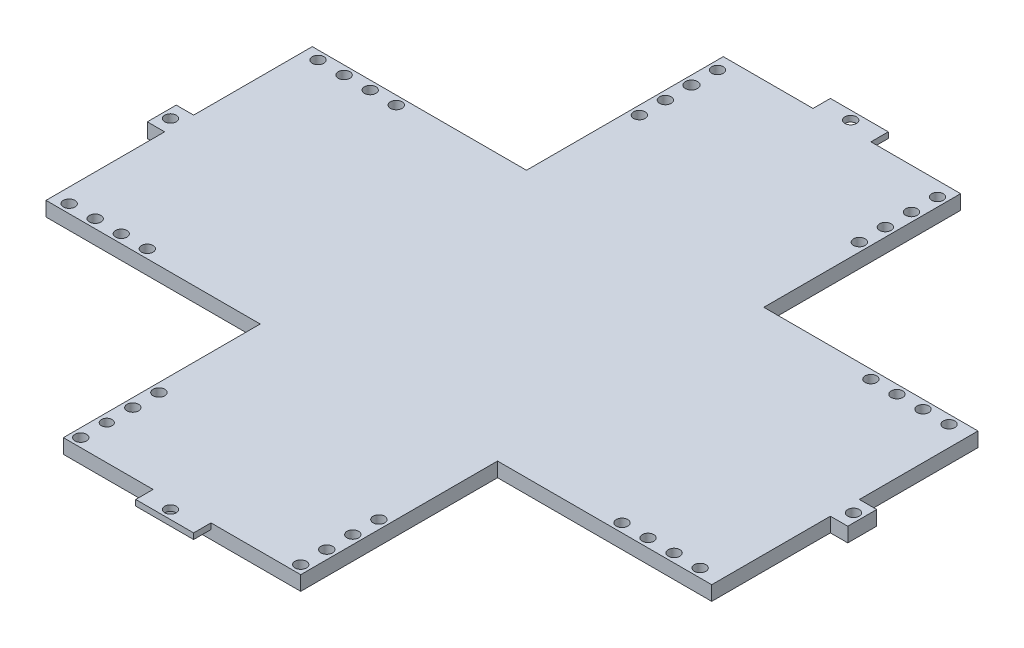
SolidWorks part; units mm, degrees
ref_plane "Front Plane" through (0, 0, 0) normal (0, 0, 1) x (1, 0, 0)
ref_plane "Top Plane" through (0, 0, 0) normal (0, 1, 0) x (1, 0, 0)
ref_plane "Right Plane" through (0, 0, 0) normal (1, 0, 0) x (0, 0, -1)
sketch "Sketch1" plane through (0, 0, 0) normal (0, 1, 0) x (1, 0, 0)
  line L0 (0, 0) -> (0, 233.68)
  line L1 (203.2, 233.68) -> (0, 233.68)
  line L2 (203.2, 233.68) -> (203.2, 421.64)
  line L3 (203.2, 421.64) -> (411.48, 421.64)
  line L4 (411.48, 421.64) -> (411.48, 233.68)
  line L5 (411.48, 233.68) -> (614.68, 233.68)
  line L6 (614.68, 233.68) -> (614.68, 0)
  line L7 (614.68, 0) -> (411.48, 0)
  line L8 (411.48, 0) -> (411.48, -187.96)
  line L9 (411.48, -187.96) -> (203.2, -187.96)
  line L10 (203.2, -187.96) -> (203.2, 0)
  line L11 (203.2, 0) -> (0, 0)
  dimension "D1" = 233.68
  dimension "D2" = 208.28
  dimension "D3" = 203.2
  dimension "D4" = 187.96
  dimension "D5" = 187.96
  dimension "D6" = 203.2
  dimension "D7" = 203.2
  dimension "D8" = 233.68
  dimension "D9" = 187.96
  dimension "D10" = 187.96
  dimension "D11" = 208.28
extrude "Boss-Extrude1" add sketch "Sketch1" along normal blind 12.7
sketch "Sketch3" plane through (0, 12.7, 0) normal (0, 1, 0) x (1, 0, 0)
  line L1 (203.2, 421.64) -> (281.94, 421.64)
  line L2 (203.2, 421.64) -> (203.2, 406.4)
  line L3 (203.2, 406.4) -> (281.94, 406.4)
  line L4 (281.94, 421.64) -> (281.94, 406.4)
  line L5 (411.48, 421.64) -> (332.74, 421.64)
  line L6 (411.48, 421.64) -> (411.48, 406.4)
  line L7 (411.48, 406.4) -> (332.74, 406.4)
  line L8 (332.74, 421.64) -> (332.74, 406.4)
  line L9 (411.48, -187.96) -> (332.74, -187.96)
  line L10 (411.48, -187.96) -> (411.48, -172.72)
  line L11 (411.48, -172.72) -> (332.74, -172.72)
  line L12 (332.74, -187.96) -> (332.74, -172.72)
  line L13 (203.2, -187.96) -> (281.94, -187.96)
  line L14 (203.2, -187.96) -> (203.2, -172.72)
  line L15 (203.2, -172.72) -> (281.94, -172.72)
  line L16 (281.94, -187.96) -> (281.94, -172.72)
extrude "Cut-Extrude1" cut sketch "Sketch3" against normal blind 15.24
sketch "Sketch5" plane through (0, 0, 0) normal (0, -1, 0) x (-1, 0, 0)
  line L0 (-281.94, 421.64) -> (-281.94, 406.4) construction
  line L1 (-281.94, -187.96) -> (-332.74, -187.96)
  line L2 (-281.94, -187.96) -> (-281.94, -172.72)
  line L3 (-281.94, -172.72) -> (-332.74, -172.72)
  line L4 (-332.74, -187.96) -> (-332.74, -172.72)
  line L5 (-332.74, 421.64) -> (-281.94, 421.64)
  line L6 (-332.74, 421.64) -> (-332.74, 406.4)
  line L7 (-332.74, 406.4) -> (-281.94, 406.4)
  line L8 (-281.94, 421.64) -> (-281.94, 406.4)
extrude "Cut-Extrude2" cut sketch "Sketch5" against normal blind 7.62
sketch "Sketch6" plane through (0, 12.7, 0) normal (0, 1, 0) x (1, 0, 0)
  line L0 (281.94, -187.96) -> (332.74, -187.96) construction
  line L1 (332.74, 421.64) -> (281.94, 421.64) construction
  circle A0 centre (307.34, 414.02) radius 5.08
  circle A1 centre (304.8, -180.34) radius 5.08
  point P8 (307.34, 421.64)
  point P9 (0, 0)
  point P10 (0, 0)
  dimension "D1" = 7.62
  dimension "D2" = 7.62
extrude "Cut-Extrude3" cut sketch "Sketch6" against normal blind 10.16
sketch "Sketch7" plane through (0, 12.7, 0) normal (0, 1, 0) x (1, 0, 0)
  line L1 (0, 0) -> (15.24, 0)
  line L2 (0, 0) -> (0, 104.14)
  line L3 (0, 104.14) -> (15.24, 104.14)
  line L4 (15.24, 0) -> (15.24, 104.14)
  line L5 (0, 233.68) -> (15.24, 233.68)
  line L6 (0, 233.68) -> (0, 129.54)
  line L7 (0, 129.54) -> (15.24, 129.54)
  line L8 (15.24, 233.68) -> (15.24, 129.54)
  line L9 (614.68, 0) -> (599.44, 0)
  line L10 (614.68, 0) -> (614.68, 104.14)
  line L11 (614.68, 104.14) -> (599.44, 104.14)
  line L12 (599.44, 0) -> (599.44, 104.14)
  line L13 (614.68, 233.68) -> (599.44, 233.68)
  line L14 (614.68, 233.68) -> (614.68, 129.54)
  line L15 (614.68, 129.54) -> (599.44, 129.54)
  line L16 (599.44, 233.68) -> (599.44, 129.54)
extrude "Cut-Extrude4" cut sketch "Sketch7" against normal blind 15.24
sketch "Sketch8" plane through (0, 12.7, 0) normal (0, 1, 0) x (1, 0, 0)
  circle A0 centre (607.06, 116.84) radius 5.08
  circle A1 centre (7.62, 116.84) radius 5.08
extrude "Cut-Extrude5" cut sketch "Sketch8" against normal blind 15.24
sketch "Sketch9" plane through (0, 12.7, 0) normal (0, 1, 0) x (1, 0, 0)
  line L0 (15.24, 0) -> (15.24, 104.14) construction
  line L1 (203.2, 406.4) -> (281.94, 406.4) construction
  circle A0 centre (27.94, 226.06) radius 5.08
  circle A1 centre (50.8, 226.06) radius 5.08
  circle A2 centre (73.66, 226.06) radius 5.08
  circle A3 centre (96.52, 226.06) radius 5.08
  circle A4 centre (581.66, 226.06) radius 5.08
  circle A5 centre (558.8, 226.06) radius 5.08
  circle A6 centre (535.94, 226.06) radius 5.08
  circle A7 centre (513.08, 226.06) radius 5.08
  circle A8 centre (27.94, 7.62) radius 5.08
  circle A9 centre (50.8, 7.62) radius 5.08
  circle A10 centre (73.66, 7.62) radius 5.08
  circle A11 centre (96.52, 7.62) radius 5.08
  circle A12 centre (581.66, 7.62) radius 5.08
  circle A13 centre (558.8, 7.62) radius 5.08
  circle A14 centre (535.94, 7.62) radius 5.08
  circle A15 centre (513.08, 7.62) radius 5.08
  circle A16 centre (210.82, 393.7) radius 5.08
  circle A17 centre (403.86, 393.7) radius 5.08
  circle A18 centre (210.82, 370.84) radius 5.3751
  circle A19 centre (210.82, 347.98) radius 5.08
  circle A20 centre (210.82, 325.12) radius 5.08
  circle A21 centre (403.86, 370.84) radius 5.08
  circle A22 centre (403.86, 347.98) radius 5.08
  circle A23 centre (403.86, 325.12) radius 5.08
  circle A24 centre (210.82, -165.1) radius 5.08
  circle A25 centre (403.86, -165.1) radius 5.08
  circle A26 centre (210.82, -142.24) radius 4.7283
  circle A27 centre (210.82, -119.38) radius 5.08
  circle A28 centre (210.82, -96.52) radius 5.08
  circle A29 centre (403.86, -142.24) radius 5.08
  circle A30 centre (403.86, -119.38) radius 5.08
  circle A31 centre (403.86, -96.52) radius 5.08
  point P68 (0, 0)
  dimension "D1" = 12.7
  dimension "D2" = 12.7
extrude "Cut-Extrude6" cut sketch "Sketch9" against normal blind 15.24
